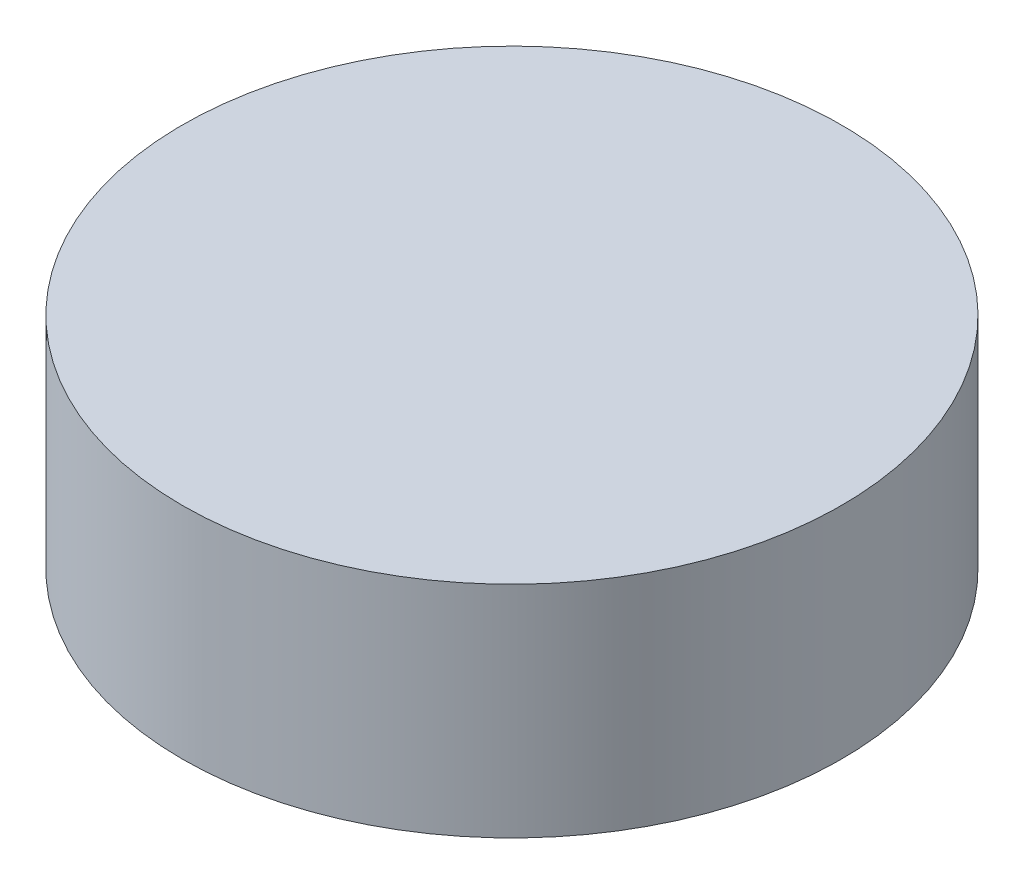
SolidWorks part; units mm, degrees
ref_plane "Ön Düzlem" through (0, 0, 0) normal (0, 0, 1) x (1, 0, 0)
ref_plane "Üst Düzlem" through (0, 0, 0) normal (0, 1, 0) x (1, 0, 0)
ref_plane "Sağ Düzlem" through (0, 0, 0) normal (1, 0, 0) x (0, 0, -1)
sketch "Çizim1" plane through (0, 0, 0) normal (0, 1, 0) x (1, 0, 0)
  circle A1 centre (0, 0) radius 30
  dimension "D2" = 60
extrude "Yükseklik-Ekstrüzyon1" add sketch "Çizim1" along normal blind 20
